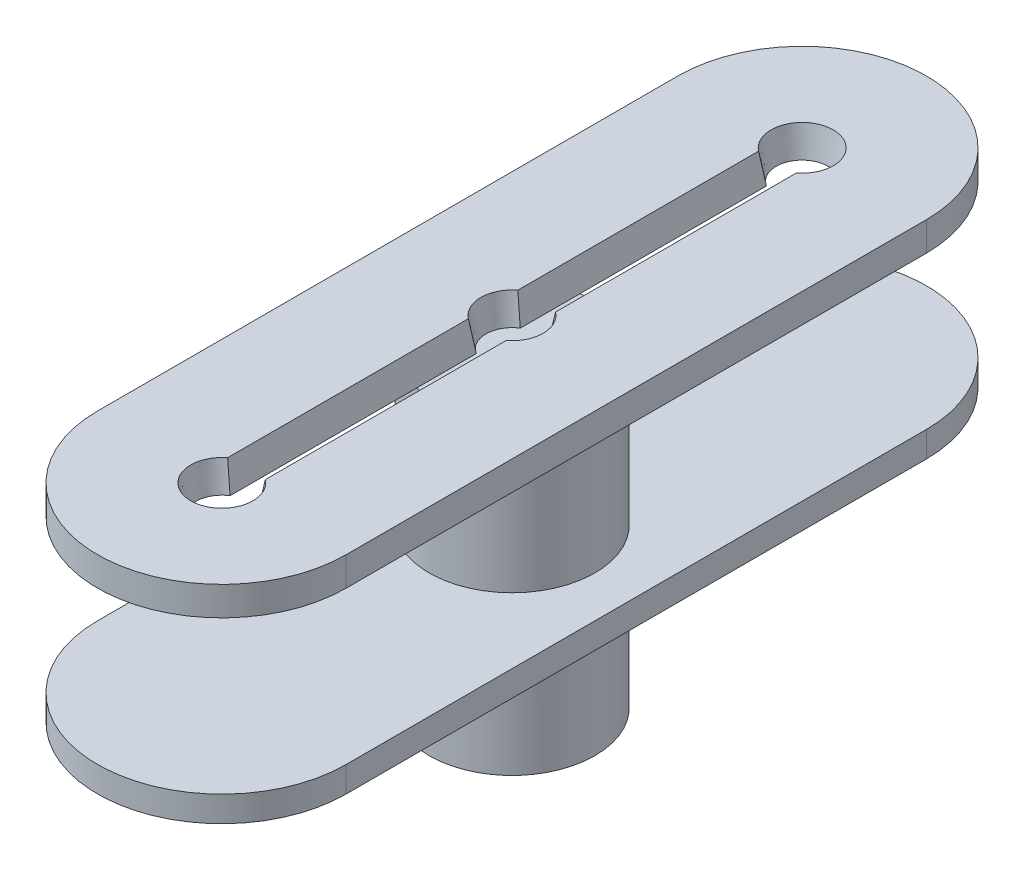
SolidWorks part; units mm, degrees
ref_plane "Alzado" through (0, 0, 0) normal (0, 0, 1) x (1, 0, 0)
ref_plane "Planta" through (0, 0, 0) normal (0, 1, 0) x (1, 0, 0)
ref_plane "Vista lateral" through (0, 0, 0) normal (1, 0, 0) x (0, 0, -1)
sketch "Croquis1" plane through (0, 0, 0) normal (0, 1, 0) x (1, 0, 0)
  line L0 (0, -7) -> (0, 7) construction
  line L1 (-3, -7) -> (-3, 7)
  line L2 (3, -7) -> (3, 7)
  arc A0 (-3, -7) -> (3, -7) centre (0, -7) ccw
  arc A1 (3, 7) -> (-3, 7) centre (0, 7) ccw
  point P3 (0, 0)
  point P8 (0, 10)
  point P9 (0, -10)
  point P10 (0, 0)
  dimension "D1" = 20
  dimension "D2" = 6
extrude "Saliente-Extruir1" add sketch "Croquis1" along normal blind 5
sketch "Croquis2" plane through (0, 5, 0) normal (0, 1, 0) x (1, 0, 0)
  line L0 (0, 10) -> (0, -10) construction
  line L3 (-0.4556, 6.4042) -> (-0.4556, 0.5958)
  line L5 (0.4556, 6.4042) -> (0.4556, 0.5958)
  line L7 (-0.4556, -0.5958) -> (-0.4556, -6.4042)
  line L9 (0.4556, -0.5958) -> (0.4556, -6.4042)
  arc A0 (3, 7) -> (-3, 7) centre (0, 7) ccw construction
  arc A1 (-3, -7) -> (3, -7) centre (0, -7) ccw construction
  arc A3 (-0.4556, 0.5958) -> (-0.4556, -0.5958) centre (0, 0) ccw
  arc A4 (-0.4556, -6.4042) -> (0.4556, -6.4042) centre (0, -7) ccw
  arc A5 (0.4556, 6.4042) -> (-0.4556, 6.4042) centre (0, 7) ccw
  arc A6 (0.4556, -0.5958) -> (0.4556, 0.5958) centre (0, 0) ccw
  point P14 (0, 0)
  point P20 (0, 0)
  point P25 (0, 0)
  point P26 (0, 0)
  point P27 (0, 0)
  dimension "D1" = 1.5
  dimension "D2" = 0.75
  dimension "D3" = 0.75
  dimension "D4" = 5.8085
  dimension "D5" = 5.8085
  dimension "D6" = 5.8085
extrude "Cortar-Extruir1" cut sketch "Croquis2" against normal blind 1 draft 10
sketch "Croquis3" plane through (3, 0, 0) normal (1, 0, 0) x (0, 0, -1)
  line L0 (-10, 5) -> (-10, 0) construction
  line L1 (-10, 4.3) -> (10, 4.3)
  line L2 (-10, 4.3) -> (-10, 0.6177)
  line L3 (-10, 0.6177) -> (10, 0.6177)
  line L4 (10, 4.3) -> (10, 0.6177)
  line L5 (10, 0) -> (10, 5) construction
  line L6 (-10, 2.4589) -> (10, 2.4589) construction
  line L7 (-7, 5) -> (7, 5) construction
  dimension "D1" = 0.7
extrude "Cortar-Extruir3" cut sketch "Croquis3" against normal through all
sketch "Croquis4" plane through (0, 4.3, 0) normal (0, -1, 0) x (1, 0, 0)
  circle A0 centre (0, 0) radius 2
  dimension "D1" = 4
extrude "Saliente-Extruir2" add sketch "Croquis4" along normal blind 7.5
